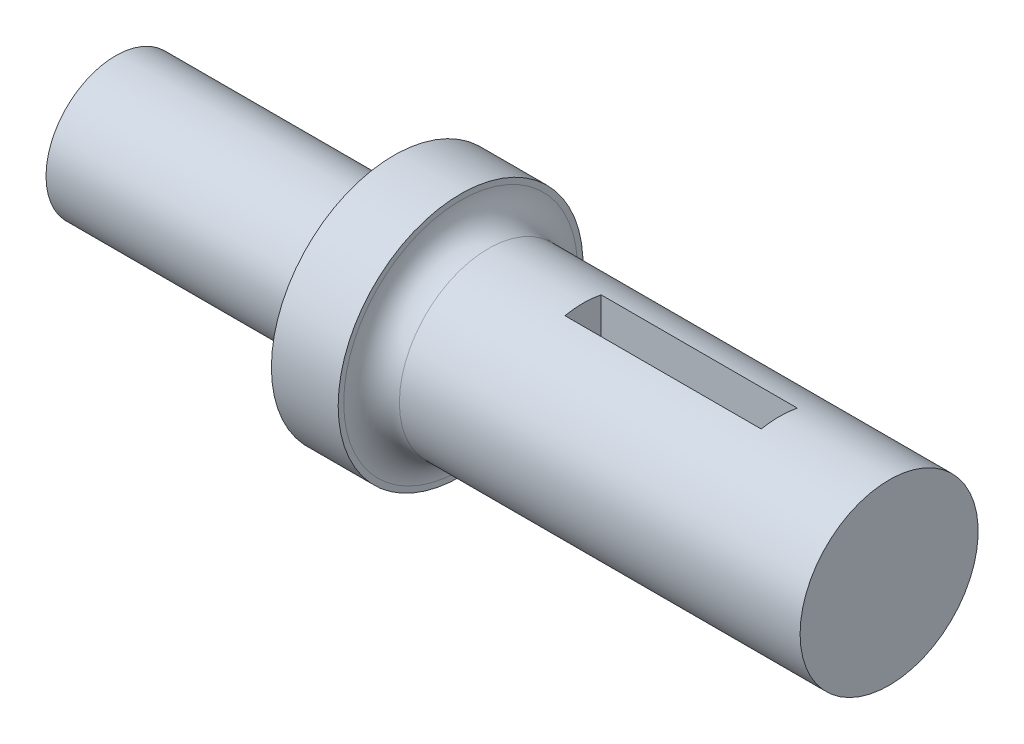
SolidWorks part; units mm, degrees
ref_plane "Front Plane" through (0, 0, 0) normal (0, 0, 1) x (1, 0, 0)
ref_plane "Top Plane" through (0, 0, 0) normal (0, 1, 0) x (1, 0, 0)
ref_plane "Right Plane" through (0, 0, 0) normal (1, 0, 0) x (0, 0, -1)
sketch "Sketch1" plane through (0, 0, 0) normal (0, 1, 0) x (1, 0, 0)
  line L0 (-139, 0) -> (0, 0)
  line L1 (0, 0) -> (0, 16)
  line L2 (0, 16) -> (-72, 16)
  line L3 (-77, 21) -> (-77, 22)
  line L4 (-77, 22) -> (-89, 22)
  line L5 (-89, 22) -> (-89, 12.5)
  line L6 (-89, 12.5) -> (-139, 12.5)
  line L7 (-139, 12.5) -> (-139, 0)
  arc A0 (-77, 21) -> (-72, 16) centre (-72, 21) ccw
  dimension "D7" = 5
  dimension "D1" = 12
  dimension "D2" = 89
  dimension "D3" = 16
  dimension "D4" = 139
  dimension "D5" = 12.5
  dimension "D6" = 22
revolve "Revolve1" add sketch "Sketch1" angle 360 about L0
sketch "Sketch2" plane through (0, 0, 0) normal (0, 0, 1) x (1, 0, 0)
  line L0 (-77, 0) -> (-55, 0)
  line L1 (-77, -21) -> (-77, 21) construction
  line L2 (-55, 0) -> (-55, 50)
  line L3 (-55, 0) -> (-55, -50)
  line L4 (-55, -50) -> (-25, -50)
  line L5 (-25, -50) -> (-17, 50)
  line L6 (-17, 50) -> (-55, 50)
  dimension "D1" = 50
  dimension "D2" = 50
  dimension "D3" = 38
  dimension "D4" = 30
  dimension "D5" = 22
extrude "Cut-Extrude1" cut sketch "Sketch2" against normal mid plane 6.5 contours L3 L4 L5 L6 L2
